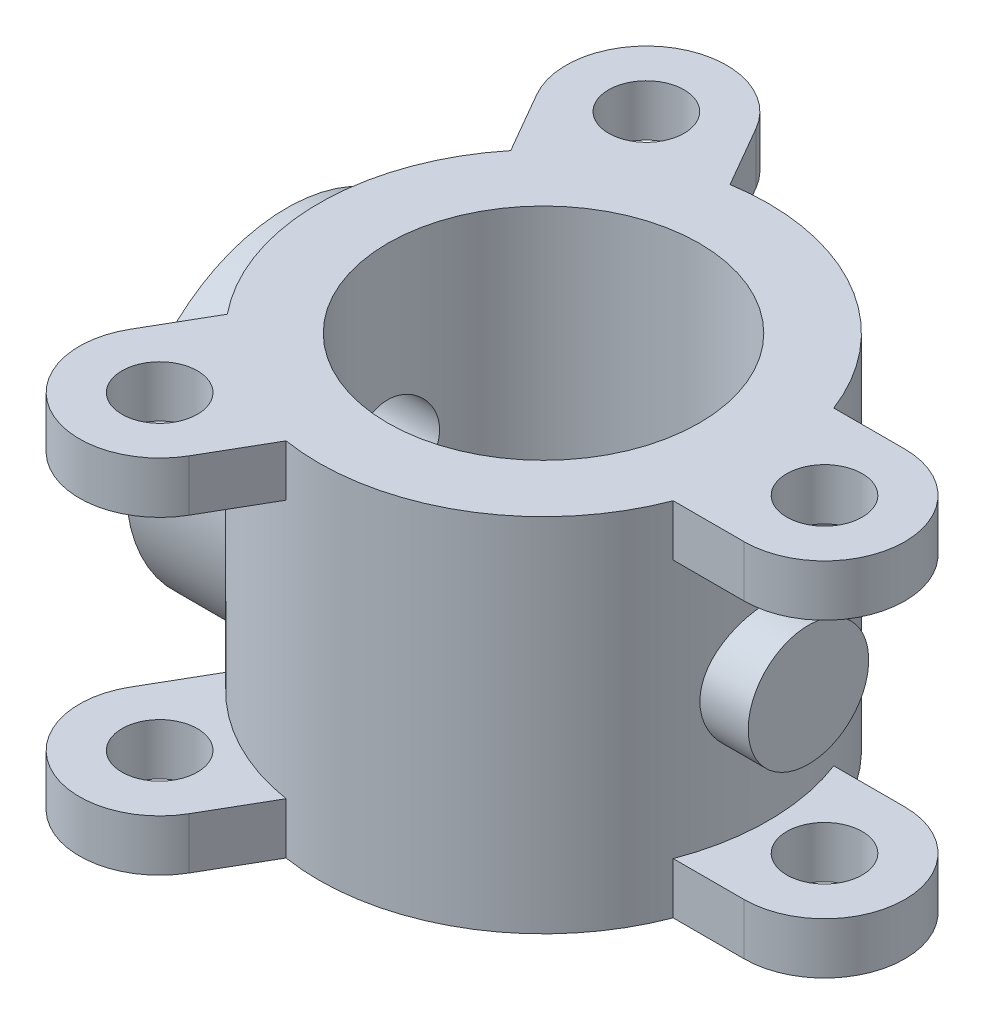
SolidWorks part; units mm, degrees
material "Gray Cast Iron"
ref_plane "Front Plane" through (0, 0, 0) normal (0, 0, 1) x (1, 0, 0)
ref_plane "Top Plane" through (0, 0, 0) normal (0, 1, 0) x (1, 0, 0)
ref_plane "Right Plane" through (0, 0, 0) normal (1, 0, 0) x (0, 0, -1)
sketch "Sketch1" plane through (0, 0, 0) normal (0, 1, 0) x (1, 0, 0)
  line L0 (-348.0839, 0) -> (348.0839, 0) construction
  line L1 (0, 268.9894) -> (0, -268.9894) construction
  line L2 (175, 50) -> (130.767, 50)
  line L3 (175, -50) -> (130.767, -50)
  line L4 (-130.8013, 126.5544) -> (-108.6848, 88.2475)
  line L5 (-44.1987, 176.5544) -> (-22.0822, 138.2475)
  line L6 (-44.1987, -176.5544) -> (-22.0822, -138.2475)
  line L7 (-130.8013, -126.5544) -> (-108.6848, -88.2475)
  line L8 (0, 0) -> (130.767, -50) construction
  line L9 (0, 0) -> (-22.0822, 138.2475) construction
  arc A0 (130.767, 50) -> (-22.0822, 138.2475) centre (0, 0) ccw
  circle A1 centre (0, 0) radius 175 construction
  arc A2 (175, -50) -> (175, 50) centre (175, 0) ccw
  circle A3 centre (175, 0) radius 23.5
  arc A4 (-44.1987, 176.5544) -> (-130.8013, 126.5544) centre (-87.5, 151.5544) ccw
  circle A5 centre (-87.5, 151.5544) radius 23.5
  arc A6 (-130.8013, -126.5544) -> (-44.1987, -176.5544) centre (-87.5, -151.5544) ccw
  circle A7 centre (-87.5, -151.5544) radius 23.5
  arc A8 (-108.6848, 88.2475) -> (-108.6848, -88.2475) centre (0, 0) ccw
  arc A9 (-22.0822, -138.2475) -> (130.767, -50) centre (0, 0) ccw
  point P7 (0, 0)
  point P10 (0, 0)
  dimension "D1" = 350
  dimension "D2" = 280
  dimension "D3" = 100
  dimension "D4" = 47
  dimension "D6" = 120
  dimension "D5" = 3
extrude "Boss-Extrude1" add sketch "Sketch1" along normal mid plane 225
sketch "Sketch2" plane through (0, 0, 0) normal (0, 1, 0) x (1, 0, 0)
  circle A0 centre (0, 0) radius 140
  dimension "D1" = 280
extrude "Cut-Extrude2" cut sketch "Sketch2" against normal mid plane 161 flip side to cut
sketch "Sketch3" plane through (0, 0, 0) normal (1, 0, 0) x (0, 0, -1)
  line L0 (88.2475, 112.5) -> (-88.2475, 112.5) construction
  circle A0 centre (0, 0) radius 100
  dimension "D1" = 200
  dimension "D2" = 112.5
extrude "Boss-Extrude2" add sketch "Sketch3" against normal blind 160
sketch "Sketch5" plane through (-160, 0, 0) normal (-1, 0, 0) x (0, 0, 1)
  circle A0 centre (0, 0) radius 37.5
  dimension "D1" = 75
extrude "Boss-Extrude3" add sketch "Sketch5" against normal blind 325
sketch "Sketch6" plane through (-160, 0, 0) normal (-1, 0, 0) x (0, 0, 1)
  circle A0 centre (0, 0) radius 28.1
  dimension "D1" = 56.2
extrude "Cut-Extrude3" cut sketch "Sketch6" against normal blind 310
sketch "Sketch7" plane through (-160, 0, 0) normal (-1, 0, 0) x (0, 0, 1)
  circle A0 centre (0, 0) radius 50
  dimension "D1" = 100
extrude "Cut-Extrude4" cut sketch "Sketch7" against normal blind 25
sketch "Sketch8" plane through (-160, 0, 0) normal (-1, 0, 0) x (0, 0, 1)
  line L0 (0, 125.8887) -> (0, -125.8887) construction
  circle A0 centre (0, 0) radius 75 construction
  circle A1 centre (0, 74.921) radius 10.15
  circle A2 centre (64.9519, -37.579) radius 10.15
  circle A3 centre (-64.9519, -37.579) radius 10.15
  circle A4 centre (0, 0) radius 50 construction
  point P5 (0, 0)
  point P14 (0, -0.079)
  dimension "D1" = 150
  dimension "D2" = 20.3
  dimension "D4" = 64.9519
  dimension "D5" = 74.921
  dimension "D3" = 3
extrude "Cut-Extrude5" cut sketch "Sketch8" against normal blind 15
sketch "Sketch9" plane through (0, 0, 0) normal (0, 1, 0) x (1, 0, 0)
  circle A0 centre (0, 0) radius 97
  dimension "D1" = 194
extrude "Cut-Extrude6" cut sketch "Sketch9" against normal through all both and the other way through all
